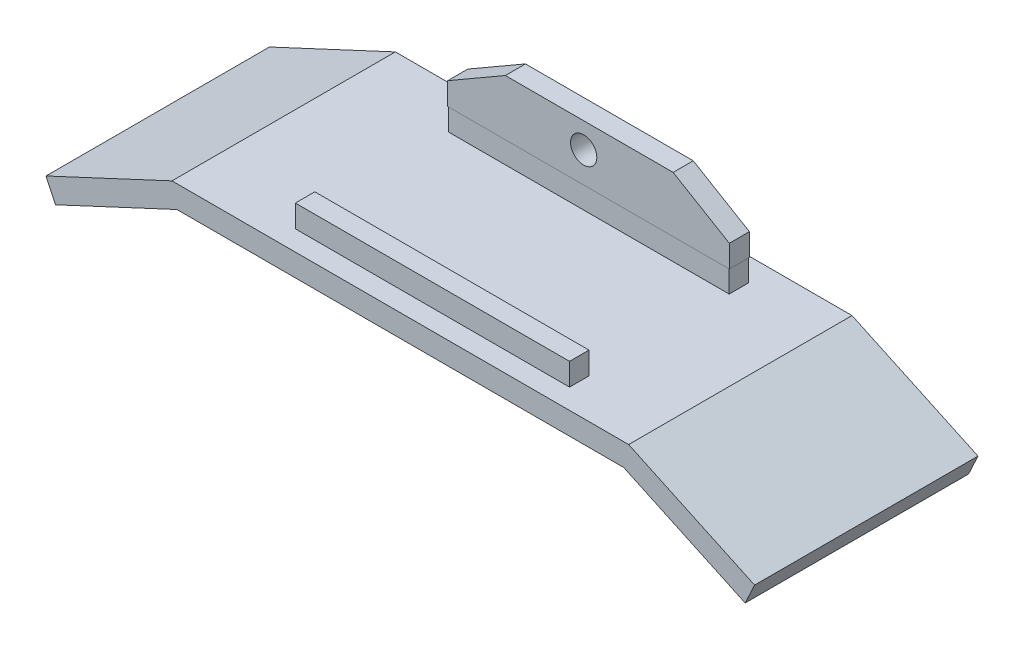
SolidWorks part; units mm, degrees
ref_plane "Front Plane" through (0, 0, 0) normal (0, 0, 1) x (1, 0, 0)
ref_plane "Top Plane" through (0, 0, 0) normal (0, 1, 0) x (1, 0, 0)
ref_plane "Right Plane" through (0, 0, 0) normal (1, 0, 0) x (0, 0, -1)
sketch "Sketch2" plane through (0, 0, 0) normal (0, 0, 1) x (1, 0, 0)
  line L0 (0, 0) -> (50.8, 0)
  line L1 (50.8, 0) -> (64.6121, -6.4407)
  line L2 (0, 0) -> (-13.8121, -6.4407)
extrude "Extrude-Thin1" add sketch "Sketch2" along normal blind 25.4 thin thin type one direction wall 2.54
sketch "Sketch3" plane through (0, 2.54, 0) normal (0, 1, 0) x (1, 0, 0)
  line L1 (10.3246, -2.6532) -> (42.264, -2.6532)
  line L2 (10.3246, -2.6532) -> (10.3246, -4.8677)
  line L3 (10.3246, -4.8677) -> (42.264, -4.8677)
  line L4 (42.264, -2.6532) -> (42.264, -4.8677)
  line L5 (10.3246, -21.9872) -> (42.3492, -21.9872)
  line L6 (10.3246, -21.9872) -> (10.3246, -19.6024) construction
  line L7 (10.3246, -19.6024) -> (42.3492, -19.6024)
  line L8 (42.3492, -21.9872) -> (42.3492, -19.6024) construction
  point P8 (0, 0)
  point P9 (42.264, -4.8677)
  point P10 (0, 0)
extrude "Boss-Extrude1" add sketch "Sketch3" along normal blind 2.54 contours L2 L1 L4 L3
sketch "Sketch4" plane through (0, 2.54, 0) normal (0, 1, 0) x (1, 0, 0)
  line L1 (11.1763, -20.8936) -> (42.3492, -20.8936)
  line L2 (11.1763, -20.8936) -> (11.1763, -23.1081)
  line L3 (11.1763, -23.1081) -> (42.3492, -23.1081)
  line L4 (42.3492, -20.8936) -> (42.3492, -23.1081)
extrude "Boss-Extrude2" add sketch "Sketch4" along normal blind 2.54
sketch "Sketch6" plane through (0, 0, 2.6532) normal (0, 0, -1) x (-1, 0, 0)
  line L0 (-42.3492, 5.08) -> (-42.3492, 7.62)
  line L1 (-42.3492, 7.62) -> (-35.9617, 11.4066)
  line L2 (-35.9617, 11.4066) -> (-16.8833, 11.4066)
  line L3 (-16.8833, 11.4066) -> (-10.3246, 7.62)
  line L4 (-10.3246, 7.62) -> (-10.3246, 5.08)
  line L5 (-42.3492, 5.08) -> (-10.3246, 5.08)
extrude "Boss-Extrude3" add sketch "Sketch6" against normal blind 2.286
sketch "Sketch10" plane through (0, 0, 4.9392) normal (0, 0, 1) x (1, 0, 0)
  circle A0 centre (25.7897, 8.5355) radius 1.4919
extrude "Cut-Extrude1" cut sketch "Sketch10" against normal through all
